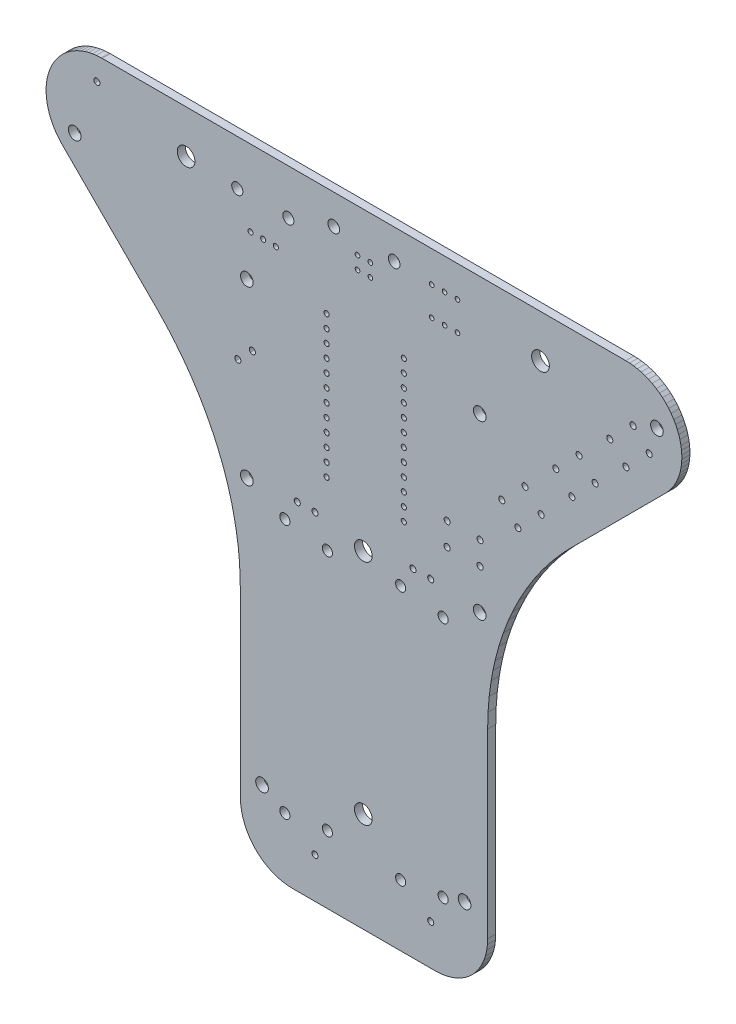
SolidWorks part; units mm, degrees
ref_plane "Front Plane" through (0, 0, 0) normal (0, 0, 1) x (1, 0, 0)
ref_plane "Top Plane" through (0, 0, 0) normal (0, 1, 0) x (1, 0, 0)
ref_plane "Right Plane" through (0, 0, 0) normal (1, 0, 0) x (0, 0, -1)
sketch "Model" plane through (0, 0, 0) normal (0, 0, 1) x (1, 0, 0)
  line L0 (-24.3003, -33.1692) -> (-24.4348, -29.3328)
  line L1 (-24.4348, -29.3328) -> (-24.7142, -26.4668)
  line L2 (-24.7142, -26.4668) -> (-25.1714, -23.5966)
  line L3 (-25.1714, -23.5966) -> (-25.5524, -21.717)
  line L4 (-25.5524, -21.717) -> (-25.9842, -19.812)
  line L5 (-25.9842, -19.812) -> (-26.7716, -17.018)
  line L6 (-26.7716, -17.018) -> (-27.7114, -14.2748)
  line L7 (-27.7114, -14.2748) -> (-28.8036, -11.557)
  line L8 (-28.8036, -11.557) -> (-29.6164, -9.779)
  line L9 (-29.6164, -9.779) -> (-30.9372, -7.1628)
  line L10 (-30.9372, -7.1628) -> (-32.4104, -4.5974)
  line L11 (-32.4104, -4.5974) -> (-33.9852, -2.1336)
  line L12 (-33.9852, -2.1336) -> (-35.1282, -0.5334)
  line L13 (-35.1282, -0.5334) -> (-36.9316, 1.8034)
  line L14 (-36.9316, 1.8034) -> (-38.862, 4.064)
  line L15 (-38.862, 4.064) -> (-40.894, 6.1976)
  line L16 (-24.3003, -33.1692) -> (-24.3003, -69.0429)
  line L17 (40.4734, 5.5013) -> (59.6982, 24.738)
  line L18 (40.4734, 5.5013) -> (39.1247, 4.0579)
  line L19 (39.1247, 4.0579) -> (37.198, 1.8116)
  line L20 (37.198, 1.8116) -> (35.3917, -0.5263)
  line L21 (35.3917, -0.5263) -> (33.7108, -2.9495)
  line L22 (33.7108, -2.9495) -> (32.1599, -5.4511)
  line L23 (32.1599, -5.4511) -> (30.7434, -8.0242)
  line L24 (30.7434, -8.0242) -> (29.4652, -10.6617)
  line L25 (29.4652, -10.6617) -> (28.6917, -12.4521)
  line L26 (28.6917, -12.4521) -> (27.6518, -15.1804)
  line L27 (27.6518, -15.1804) -> (26.7588, -17.9532)
  line L28 (26.7588, -17.9532) -> (26.0152, -20.7626)
  line L29 (26.0152, -20.7626) -> (25.6035, -22.6521)
  line L30 (25.6035, -22.6521) -> (25.2596, -24.5522)
  line L31 (25.2596, -24.5522) -> (24.8719, -27.4168)
  line L32 (24.8719, -27.4168) -> (24.6388, -30.2918)
  line L33 (24.6388, -30.2918) -> (24.561, -33.1692)
  line L34 (24.561, -69.0429) -> (24.561, -33.1692)
  line L35 (14.3787, -79.7108) -> (15.5547, -79.6255)
  line L36 (15.5547, -79.6255) -> (16.5154, -79.4573)
  line L37 (16.5154, -79.4573) -> (17.4506, -79.2021)
  line L38 (17.4506, -79.2021) -> (18.3534, -78.8618)
  line L39 (18.3534, -78.8618) -> (19.3842, -78.3449)
  line L40 (19.3842, -78.3449) -> (20.1917, -77.8275)
  line L41 (20.1917, -77.8275) -> (20.946, -77.2355)
  line L42 (20.946, -77.2355) -> (21.6411, -76.5734)
  line L43 (21.6411, -76.5734) -> (22.272, -75.8462)
  line L44 (22.272, -75.8462) -> (22.8337, -75.0595)
  line L45 (22.8337, -75.0595) -> (23.3221, -74.2191)
  line L46 (23.3221, -74.2191) -> (23.806, -73.1491)
  line L47 (23.806, -73.1491) -> (24.1207, -72.2139)
  line L48 (24.1207, -72.2139) -> (24.3884, -71.05)
  line L49 (24.3884, -71.05) -> (24.5178, -70.0542)
  line L50 (24.5178, -70.0542) -> (24.561, -69.0429)
  line L51 (-13.9204, -79.7126) -> (14.1811, -79.7126)
  line L52 (-24.2986, -69.246) -> (-24.2381, -70.2549)
  line L53 (-24.2381, -70.2549) -> (-24.0519, -71.4423)
  line L54 (-24.0519, -71.4423) -> (-23.8036, -72.4037)
  line L55 (-23.8036, -72.4037) -> (-23.4726, -73.3316)
  line L56 (-23.4726, -73.3316) -> (-23.0614, -74.2191)
  line L57 (-23.0614, -74.2191) -> (-22.573, -75.0595)
  line L58 (-22.573, -75.0595) -> (-22.0113, -75.8462)
  line L59 (-22.0113, -75.8462) -> (-21.2464, -76.7112)
  line L60 (-21.2464, -76.7112) -> (-20.5389, -77.3596)
  line L61 (-20.5389, -77.3596) -> (-19.7736, -77.9371)
  line L62 (-19.7736, -77.9371) -> (-18.7869, -78.53)
  line L63 (-18.7869, -78.53) -> (-17.9151, -78.9365)
  line L64 (-17.9151, -78.9365) -> (-16.8193, -79.3145)
  line L65 (-16.8193, -79.3145) -> (-15.873, -79.5351)
  line L66 (-15.873, -79.5351) -> (-14.9043, -79.6681)
  line L67 (-14.9043, -79.6681) -> (-13.9204, -79.7126)
  line L68 (-59.4375, 24.738) -> (-40.9057, 6.2062)
  line L69 (-51.7634, 43.4849) -> (-52.727, 43.4265)
  line L70 (-52.727, 43.4265) -> (-53.4919, 43.32)
  line L71 (-53.4919, 43.32) -> (-54.2475, 43.1609)
  line L72 (-54.2475, 43.1609) -> (-54.9901, 42.9499)
  line L73 (-54.9901, 42.9499) -> (-55.716, 42.6882)
  line L74 (-55.716, 42.6882) -> (-56.4219, 42.3768)
  line L75 (-56.4219, 42.3768) -> (-57.1042, 42.0175)
  line L76 (-57.1042, 42.0175) -> (-57.9188, 41.5034)
  line L77 (-57.9188, 41.5034) -> (-58.5362, 41.0428)
  line L78 (-58.5362, 41.0428) -> (-59.1197, 40.5405)
  line L79 (-59.1197, 40.5405) -> (-59.6666, 39.9992)
  line L80 (-59.6666, 39.9992) -> (-60.1741, 39.4214)
  line L81 (-60.1741, 39.4214) -> (-60.6399, 38.8099)
  line L82 (-60.6399, 38.8099) -> (-61.0616, 38.1676)
  line L83 (-61.0616, 38.1676) -> (-61.4372, 37.4978)
  line L84 (-61.4372, 37.4978) -> (-61.8391, 36.6267)
  line L85 (-61.8391, 36.6267) -> (-62.1048, 35.9069)
  line L86 (-62.1048, 35.9069) -> (-62.3647, 34.9843)
  line L87 (-62.3647, 34.9843) -> (-62.5137, 34.2321)
  line L88 (-62.5137, 34.2321) -> (-62.6097, 33.4715)
  line L89 (-62.6097, 33.4715) -> (-62.652, 32.7061)
  line L90 (-62.652, 32.7061) -> (-62.6405, 31.9396)
  line L91 (-62.6405, 31.9396) -> (-62.5752, 31.1758)
  line L92 (-62.5752, 31.1758) -> (-62.4565, 30.4184)
  line L93 (-62.4565, 30.4184) -> (-62.2339, 29.4861)
  line L94 (-62.2339, 29.4861) -> (-61.9974, 28.7564)
  line L95 (-61.9974, 28.7564) -> (-61.7103, 28.0447)
  line L96 (-61.7103, 28.0447) -> (-61.374, 27.3547)
  line L97 (-61.374, 27.3547) -> (-60.8869, 26.5275)
  line L98 (-60.8869, 26.5275) -> (-60.4461, 25.898)
  line L99 (-60.4461, 25.898) -> (-59.9622, 25.3006)
  line L100 (-59.9622, 25.3006) -> (-59.4375, 24.738)
  line L101 (51.831, 43.4866) -> (-51.5703, 43.4866)
  line L102 (59.8331, 24.8752) -> (60.3478, 25.4468)
  line L103 (60.3478, 25.4468) -> (60.9327, 26.209)
  line L104 (60.9327, 26.209) -> (61.3512, 26.8533)
  line L105 (61.3512, 26.8533) -> (61.7233, 27.525)
  line L106 (61.7233, 27.525) -> (62.0475, 28.2207)
  line L107 (62.0475, 28.2207) -> (62.3221, 28.9372)
  line L108 (62.3221, 28.9372) -> (62.5457, 29.671)
  line L109 (62.5457, 29.671) -> (62.7519, 30.6069)
  line L110 (62.7519, 30.6069) -> (62.8573, 31.3663)
  line L111 (62.8573, 31.3663) -> (62.9091, 32.1311)
  line L112 (62.9091, 32.1311) -> (62.9072, 32.8977)
  line L113 (62.9072, 32.8977) -> (62.8514, 33.6622)
  line L114 (62.8514, 33.6622) -> (62.7422, 34.4211)
  line L115 (62.7422, 34.4211) -> (62.5312, 35.356)
  line L116 (62.5312, 35.356) -> (62.3038, 36.0886)
  line L117 (62.3038, 36.0886) -> (62.0256, 36.8037)
  line L118 (62.0256, 36.8037) -> (61.6979, 37.4978)
  line L119 (61.6979, 37.4978) -> (61.3223, 38.1676)
  line L120 (61.3223, 38.1676) -> (60.7882, 38.9657)
  line L121 (60.7882, 38.9657) -> (60.3117, 39.5691)
  line L122 (60.3117, 39.5691) -> (59.7941, 40.138)
  line L123 (59.7941, 40.138) -> (59.093, 40.7967)
  line L124 (59.093, 40.7967) -> (58.4923, 41.2785)
  line L125 (58.4923, 41.2785) -> (57.8591, 41.7175)
  line L126 (57.8591, 41.7175) -> (57.0269, 42.2031)
  line L127 (57.0269, 42.2031) -> (56.3324, 42.5386)
  line L128 (56.3324, 42.5386) -> (55.6161, 42.8253)
  line L129 (55.6161, 42.8253) -> (54.8814, 43.0618)
  line L130 (54.8814, 43.0618) -> (54.1318, 43.247)
  line L131 (54.1318, 43.247) -> (53.3711, 43.3799)
  line L132 (53.3711, 43.3799) -> (52.603, 43.4599)
  line L133 (52.603, 43.4599) -> (51.831, 43.4866)
  line L134 (-7.2415, -6.477) -> (-7.2365, -6.477)
  line L135 (-24.3003, -69.0429) -> (-24.2986, -69.246)
  line L136 (-7.2415, -5.461) -> (-7.2365, -5.461)
  line L137 (-40.9057, 6.2062) -> (-40.894, 6.1976)
  line L138 (-7.2415, -3.937) -> (-7.2365, -3.937)
  line L139 (59.6982, 24.738) -> (59.8331, 24.8752)
  line L140 (-7.2415, -2.921) -> (-7.2365, -2.921)
  line L141 (14.1811, -79.7126) -> (14.3787, -79.7108)
  line L142 (-7.2415, -1.397) -> (-7.2365, -1.397)
  line L143 (-51.7634, 43.4849) -> (-51.5703, 43.4866)
  line L144 (-7.2415, -0.381) -> (-7.2365, -0.381)
  line L146 (-7.2415, 1.143) -> (-7.2365, 1.143)
  line L148 (-7.2415, 2.159) -> (-7.2365, 2.159)
  line L150 (-7.2415, 3.683) -> (-7.2365, 3.683)
  line L152 (-7.2415, 4.699) -> (-7.2365, 4.699)
  line L154 (-7.2415, 6.223) -> (-7.2365, 6.223)
  line L156 (-7.2415, 7.239) -> (-7.2365, 7.239)
  line L158 (-7.2415, 8.763) -> (-7.2365, 8.763)
  line L160 (-7.2415, 9.779) -> (-7.2365, 9.779)
  line L162 (-7.2415, 11.303) -> (-7.2365, 11.303)
  line L164 (-7.2415, 12.319) -> (-7.2365, 12.319)
  line L166 (-7.2415, 13.843) -> (-7.2365, 13.843)
  line L168 (-7.2415, 14.859) -> (-7.2365, 14.859)
  line L170 (-7.2415, 16.383) -> (-7.2365, 16.383)
  line L172 (-7.2415, 17.399) -> (-7.2365, 17.399)
  line L174 (-7.2415, 18.923) -> (-7.2365, 18.923)
  line L176 (-7.2415, 19.939) -> (-7.2365, 19.939)
  line L178 (-7.2415, 21.463) -> (-7.2365, 21.463)
  line L180 (-7.2415, 22.479) -> (-7.2365, 22.479)
  line L182 (8.0035, 22.479) -> (7.9985, 22.479)
  line L184 (8.0035, 21.463) -> (7.9985, 21.463)
  line L186 (8.0035, 19.939) -> (7.9985, 19.939)
  line L188 (8.0035, 18.923) -> (7.9985, 18.923)
  line L190 (8.0035, 17.399) -> (7.9985, 17.399)
  line L192 (8.0035, 16.383) -> (7.9985, 16.383)
  line L194 (8.0035, 14.859) -> (7.9985, 14.859)
  line L196 (8.0035, 13.843) -> (7.9985, 13.843)
  line L198 (8.0035, 12.319) -> (7.9985, 12.319)
  line L200 (8.0035, 11.303) -> (7.9985, 11.303)
  line L202 (8.0035, 9.779) -> (7.9985, 9.779)
  line L204 (8.0035, 8.763) -> (7.9985, 8.763)
  line L206 (8.0035, 7.239) -> (7.9985, 7.239)
  line L208 (8.0035, 6.223) -> (7.9985, 6.223)
  line L210 (8.0035, 4.699) -> (7.9985, 4.699)
  line L212 (8.0035, 3.683) -> (7.9985, 3.683)
  line L214 (8.0035, 2.159) -> (7.9985, 2.159)
  line L216 (8.0035, 1.143) -> (7.9985, 1.143)
  line L218 (8.0035, -0.381) -> (7.9985, -0.381)
  line L220 (8.0035, -1.397) -> (7.9985, -1.397)
  line L222 (8.0035, -2.921) -> (7.9985, -2.921)
  line L224 (8.0035, -3.937) -> (7.9985, -3.937)
  line L226 (8.0035, -5.461) -> (7.9985, -5.461)
  line L228 (8.0035, -6.477) -> (7.9985, -6.477)
  line L230 (-10.144, -13.1244) -> (-10.144, -13.1194)
  line L232 (-8.9441, -13.1244) -> (-8.9441, -13.1194)
  line L234 (-13.6441, -13.1244) -> (-13.6441, -13.1194)
  line L236 (-12.4442, -13.1244) -> (-12.4442, -13.1194)
  line L238 (-10.144, -71.7166) -> (-10.144, -71.7116)
  line L240 (-8.9441, -71.7166) -> (-8.9441, -71.7116)
  line L242 (-8.0942, -66.3666) -> (-8.0942, -66.3616)
  line L244 (-6.0942, -66.3666) -> (-6.0942, -66.3616)
  line L246 (-8.0942, -18.4744) -> (-8.0942, -18.4694)
  line L248 (-6.0942, -18.4744) -> (-6.0942, -18.4694)
  line L250 (-16.494, -17.2745) -> (-16.494, -17.2695)
  line L252 (-14.494, -17.2745) -> (-14.494, -17.2695)
  line L254 (-16.494, -67.5665) -> (-16.494, -67.5615)
  line L256 (-14.494, -67.5665) -> (-14.494, -67.5615)
  line L258 (12.716, -13.1244) -> (12.716, -13.1194)
  line L260 (13.9159, -13.1244) -> (13.9159, -13.1194)
  line L262 (9.2159, -13.1244) -> (9.2159, -13.1194)
  line L264 (10.4158, -13.1244) -> (10.4158, -13.1194)
  line L266 (12.716, -71.7166) -> (12.716, -71.7116)
  line L268 (13.9159, -71.7166) -> (13.9159, -71.7116)
  line L270 (14.7658, -66.3666) -> (14.7658, -66.3616)
  line L272 (16.7658, -66.3666) -> (16.7658, -66.3616)
  line L274 (14.7658, -18.4744) -> (14.7658, -18.4694)
  line L276 (16.7658, -18.4744) -> (16.7658, -18.4694)
  line L278 (6.366, -17.2745) -> (6.366, -17.2695)
  line L280 (8.366, -17.2745) -> (8.366, -17.2695)
  line L282 (6.366, -67.5665) -> (6.366, -67.5615)
  line L284 (8.366, -67.5665) -> (8.366, -67.5615)
  line L286 (-22.3307, 7.846) -> (-22.3272, 7.8424)
  line L288 (-21.4823, 8.6944) -> (-21.4787, 8.6908)
  line L290 (-25.2044, 4.9723) -> (-25.2008, 4.9687)
  line L292 (-24.356, 5.8207) -> (-24.3524, 5.8172)
  line L294 (-53.0432, 38.5584) -> (-53.0396, 38.5549)
  line L296 (-52.1948, 39.4069) -> (-52.1912, 39.4033)
  circle A0 centre (23.0619, -6.0599) radius 0.5999
  circle A2 centre (16.5621, -6.0599) radius 0.5999
  circle A4 centre (16.5621, -1.5601) radius 0.5999
  circle A6 centre (23.0619, -1.5601) radius 0.5999
  circle A8 centre (-1.143, 35.052) radius 0.46
  circle A10 centre (-1.143, 32.512) radius 0.46
  circle A12 centre (1.397, 35.052) radius 0.46
  circle A14 centre (6.096, 37.592) radius 1.15
  circle A16 centre (-5.842, 37.592) radius 1.15
  arc A18 (-7.2365, -6.477) -> (-7.2365, -5.461) centre (-7.2365, -5.969) ccw
  arc A19 (-7.2415, -5.461) -> (-7.2415, -6.477) centre (-7.2415, -5.969) ccw
  arc A21 (-7.2365, -3.937) -> (-7.2365, -2.921) centre (-7.2365, -3.429) ccw
  arc A22 (-7.2415, -2.921) -> (-7.2415, -3.937) centre (-7.2415, -3.429) ccw
  arc A24 (-7.2365, -1.397) -> (-7.2365, -0.381) centre (-7.2365, -0.889) ccw
  arc A25 (-7.2415, -0.381) -> (-7.2415, -1.397) centre (-7.2415, -0.889) ccw
  arc A27 (-7.2365, 1.143) -> (-7.2365, 2.159) centre (-7.2365, 1.651) ccw
  arc A28 (-7.2415, 2.159) -> (-7.2415, 1.143) centre (-7.2415, 1.651) ccw
  arc A30 (-7.2365, 3.683) -> (-7.2365, 4.699) centre (-7.2365, 4.191) ccw
  arc A31 (-7.2415, 4.699) -> (-7.2415, 3.683) centre (-7.2415, 4.191) ccw
  arc A33 (-7.2365, 6.223) -> (-7.2365, 7.239) centre (-7.2365, 6.731) ccw
  arc A34 (-7.2415, 7.239) -> (-7.2415, 6.223) centre (-7.2415, 6.731) ccw
  arc A36 (-7.2365, 8.763) -> (-7.2365, 9.779) centre (-7.2365, 9.271) ccw
  arc A37 (-7.2415, 9.779) -> (-7.2415, 8.763) centre (-7.2415, 9.271) ccw
  arc A39 (-7.2365, 11.303) -> (-7.2365, 12.319) centre (-7.2365, 11.811) ccw
  arc A40 (-7.2415, 12.319) -> (-7.2415, 11.303) centre (-7.2415, 11.811) ccw
  arc A42 (-7.2365, 13.843) -> (-7.2365, 14.859) centre (-7.2365, 14.351) ccw
  arc A43 (-7.2415, 14.859) -> (-7.2415, 13.843) centre (-7.2415, 14.351) ccw
  arc A45 (-7.2365, 16.383) -> (-7.2365, 17.399) centre (-7.2365, 16.891) ccw
  arc A46 (-7.2415, 17.399) -> (-7.2415, 16.383) centre (-7.2415, 16.891) ccw
  arc A48 (-7.2365, 18.923) -> (-7.2365, 19.939) centre (-7.2365, 19.431) ccw
  arc A49 (-7.2415, 19.939) -> (-7.2415, 18.923) centre (-7.2415, 19.431) ccw
  arc A51 (-7.2365, 21.463) -> (-7.2365, 22.479) centre (-7.2365, 21.971) ccw
  arc A52 (-7.2415, 22.479) -> (-7.2415, 21.463) centre (-7.2415, 21.971) ccw
  arc A54 (7.9985, 22.479) -> (7.9985, 21.463) centre (7.9985, 21.971) ccw
  arc A55 (8.0035, 21.463) -> (8.0035, 22.479) centre (8.0035, 21.971) ccw
  arc A57 (7.9985, 19.939) -> (7.9985, 18.923) centre (7.9985, 19.431) ccw
  arc A58 (8.0035, 18.923) -> (8.0035, 19.939) centre (8.0035, 19.431) ccw
  arc A60 (7.9985, 17.399) -> (7.9985, 16.383) centre (7.9985, 16.891) ccw
  arc A61 (8.0035, 16.383) -> (8.0035, 17.399) centre (8.0035, 16.891) ccw
  arc A63 (7.9985, 14.859) -> (7.9985, 13.843) centre (7.9985, 14.351) ccw
  arc A64 (8.0035, 13.843) -> (8.0035, 14.859) centre (8.0035, 14.351) ccw
  arc A66 (7.9985, 12.319) -> (7.9985, 11.303) centre (7.9985, 11.811) ccw
  arc A67 (8.0035, 11.303) -> (8.0035, 12.319) centre (8.0035, 11.811) ccw
  arc A69 (7.9985, 9.779) -> (7.9985, 8.763) centre (7.9985, 9.271) ccw
  arc A70 (8.0035, 8.763) -> (8.0035, 9.779) centre (8.0035, 9.271) ccw
  arc A72 (7.9985, 7.239) -> (7.9985, 6.223) centre (7.9985, 6.731) ccw
  arc A73 (8.0035, 6.223) -> (8.0035, 7.239) centre (8.0035, 6.731) ccw
  arc A75 (7.9985, 4.699) -> (7.9985, 3.683) centre (7.9985, 4.191) ccw
  arc A76 (8.0035, 3.683) -> (8.0035, 4.699) centre (8.0035, 4.191) ccw
  arc A78 (7.9985, 2.159) -> (7.9985, 1.143) centre (7.9985, 1.651) ccw
  arc A79 (8.0035, 1.143) -> (8.0035, 2.159) centre (8.0035, 1.651) ccw
  arc A81 (7.9985, -0.381) -> (7.9985, -1.397) centre (7.9985, -0.889) ccw
  arc A82 (8.0035, -1.397) -> (8.0035, -0.381) centre (8.0035, -0.889) ccw
  arc A84 (7.9985, -2.921) -> (7.9985, -3.937) centre (7.9985, -3.429) ccw
  arc A85 (8.0035, -3.937) -> (8.0035, -2.921) centre (8.0035, -3.429) ccw
  arc A87 (7.9985, -5.461) -> (7.9985, -6.477) centre (7.9985, -5.969) ccw
  arc A88 (8.0035, -6.477) -> (8.0035, -5.461) centre (8.0035, -5.969) ccw
  arc A90 (-8.9441, -13.1194) -> (-10.144, -13.1194) centre (-9.544, -13.1194) ccw
  arc A91 (-10.144, -13.1244) -> (-8.9441, -13.1244) centre (-9.544, -13.1244) ccw
  arc A93 (-12.4442, -13.1194) -> (-13.6441, -13.1194) centre (-13.0442, -13.1194) ccw
  arc A94 (-13.6441, -13.1244) -> (-12.4442, -13.1244) centre (-13.0442, -13.1244) ccw
  arc A96 (-8.9441, -71.7116) -> (-10.144, -71.7116) centre (-9.544, -71.7116) ccw
  arc A97 (-10.144, -71.7166) -> (-8.9441, -71.7166) centre (-9.544, -71.7166) ccw
  arc A99 (-6.0942, -66.3616) -> (-8.0942, -66.3616) centre (-7.0942, -66.3616) ccw
  arc A100 (-8.0942, -66.3666) -> (-6.0942, -66.3666) centre (-7.0942, -66.3666) ccw
  arc A102 (-6.0942, -18.4694) -> (-8.0942, -18.4694) centre (-7.0942, -18.4694) ccw
  arc A103 (-8.0942, -18.4744) -> (-6.0942, -18.4744) centre (-7.0942, -18.4744) ccw
  arc A105 (-14.494, -17.2695) -> (-16.494, -17.2695) centre (-15.494, -17.2695) ccw
  arc A106 (-16.494, -17.2745) -> (-14.494, -17.2745) centre (-15.494, -17.2745) ccw
  arc A108 (-14.494, -67.5615) -> (-16.494, -67.5615) centre (-15.494, -67.5615) ccw
  arc A109 (-16.494, -67.5665) -> (-14.494, -67.5665) centre (-15.494, -67.5665) ccw
  arc A111 (13.9159, -13.1194) -> (12.716, -13.1194) centre (13.3159, -13.1194) ccw
  arc A112 (12.716, -13.1244) -> (13.9159, -13.1244) centre (13.3159, -13.1244) ccw
  arc A114 (10.4158, -13.1194) -> (9.2159, -13.1194) centre (9.8158, -13.1194) ccw
  arc A115 (9.2159, -13.1244) -> (10.4158, -13.1244) centre (9.8158, -13.1244) ccw
  arc A117 (13.9159, -71.7116) -> (12.716, -71.7116) centre (13.3159, -71.7116) ccw
  arc A118 (12.716, -71.7166) -> (13.9159, -71.7166) centre (13.3159, -71.7166) ccw
  arc A120 (16.7658, -66.3616) -> (14.7658, -66.3616) centre (15.7658, -66.3616) ccw
  arc A121 (14.7658, -66.3666) -> (16.7658, -66.3666) centre (15.7658, -66.3666) ccw
  arc A123 (16.7658, -18.4694) -> (14.7658, -18.4694) centre (15.7658, -18.4694) ccw
  arc A124 (14.7658, -18.4744) -> (16.7658, -18.4744) centre (15.7658, -18.4744) ccw
  arc A126 (8.366, -17.2695) -> (6.366, -17.2695) centre (7.366, -17.2695) ccw
  arc A127 (6.366, -17.2745) -> (8.366, -17.2745) centre (7.366, -17.2745) ccw
  arc A129 (8.366, -67.5615) -> (6.366, -67.5615) centre (7.366, -67.5615) ccw
  arc A130 (6.366, -67.5665) -> (8.366, -67.5665) centre (7.366, -67.5665) ccw
  arc A132 (-22.3272, 7.8424) -> (-21.4787, 8.6908) centre (-21.9029, 8.2666) ccw
  arc A133 (-21.4823, 8.6944) -> (-22.3307, 7.846) centre (-21.9065, 8.2702) ccw
  arc A135 (-25.2008, 4.9687) -> (-24.3524, 5.8172) centre (-24.7766, 5.3929) ccw
  arc A136 (-24.356, 5.8207) -> (-25.2044, 4.9723) centre (-24.7802, 5.3965) ccw
  arc A138 (-53.0396, 38.5549) -> (-52.1912, 39.4033) centre (-52.6154, 38.9791) ccw
  arc A139 (-52.1948, 39.4069) -> (-53.0432, 38.5584) centre (-52.619, 38.9827) ccw
  circle A141 centre (-14.812, 34.544) radius 1.1
  circle A143 centre (-22.2707, 28.4481) radius 0.5
  circle A145 centre (-19.7714, 28.4481) radius 0.5
  circle A147 centre (-17.272, 28.4481) radius 0.5
  circle A149 centre (-24.892, 34.544) radius 1.1
  circle A151 centre (16.0518, 37.344) radius 0.4572
  circle A153 centre (18.602, 37.344) radius 0.4572
  circle A155 centre (18.6023, 31.644) radius 0.4572
  circle A157 centre (16.0521, 31.644) radius 0.4572
  circle A159 centre (13.502, 31.644) radius 0.4572
  circle A161 centre (30.5349, 4.239) radius 0.5999
  circle A163 centre (35.131, 8.8351) radius 0.5999
  circle A165 centre (31.9491, 12.017) radius 0.5999
  circle A167 centre (27.353, 7.4209) radius 0.5999
  circle A169 centre (41.2029, 14.907) radius 0.5999
  circle A171 centre (45.799, 19.5031) radius 0.5999
  circle A173 centre (42.6171, 22.685) radius 0.5999
  circle A175 centre (38.021, 18.0889) radius 0.5999
  circle A177 centre (51.8709, 25.321) radius 0.5999
  circle A179 centre (56.467, 29.9171) radius 0.5999
  circle A181 centre (53.2851, 33.099) radius 0.5999
  circle A183 centre (48.689, 28.5029) radius 0.5999
  circle A185 centre (1.397, 32.512) radius 0.46
  circle A186 centre (13.5018, 37.3439) radius 0.4572
  circle A187 centre (0, -60.0001) radius 1.75
  circle A188 centre (0, -15) radius 1.75
  circle A189 centre (-34.9999, 34.9999) radius 1.75
  circle A190 centre (34.9999, 34.9999) radius 1.75
  circle A191 centre (20, -65.0001) radius 1.25
  circle A192 centre (-20, -65.0001) radius 1.25
  circle A193 centre (23, -14) radius 1.25
  circle A194 centre (-23, -14) radius 1.25
  circle A195 centre (23, 20) radius 1.25
  circle A196 centre (-23, 20) radius 1.25
  circle A197 centre (-56.9999, 27.9999) radius 1.25
  circle A198 centre (58.0001, 34.9999) radius 1.25
extrude "Boss-Extrude1" add sketch "Model" along normal blind 1.6
